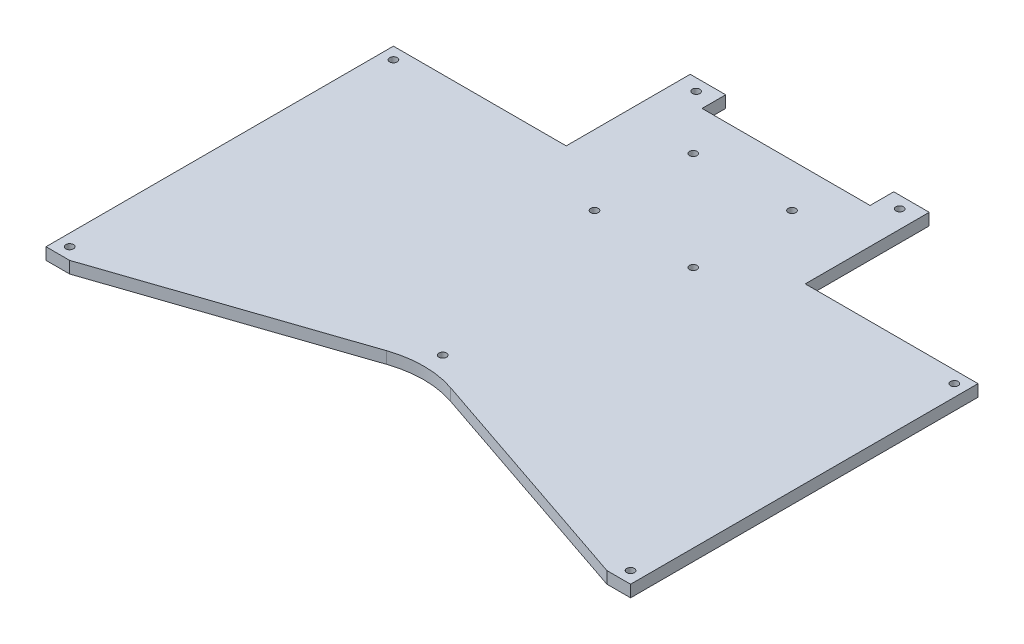
SolidWorks part; units mm, degrees
material "ABS PC"
ref_plane "Plan de face" through (0, 0, 0) normal (0, 0, 1) x (1, 0, 0)
ref_plane "Plan de dessus" through (0, 0, 0) normal (0, 1, 0) x (1, 0, 0)
ref_plane "Plan de droite" through (0, 0, 0) normal (1, 0, 0) x (0, 0, -1)
sketch "Esquisse1" plane through (0, 0, 0) normal (0, 1, 0) x (1, 0, 0)
  line L1 (-50.5, 31.2) -> (-35.5, 31.2)
  line L2 (123.5, -21.2) -> (123.5, -168)
  line L4 (123.5, -168) -> (113.5, -168)
  line L5 (-123.5, -168) -> (-123.5, -21.2)
  line L6 (-113.5, -168) -> (-123.5, -168)
  line L7 (-113.5, -168) -> (-13.4883, -134.0848)
  line L11 (13.4883, -134.0848) -> (113.5, -168)
  line L12 (-123.5, -21.2) -> (-50.5, -21.2)
  line L13 (-55.5, -15) -> (-55.5, 15) construction
  line L14 (123.5, -21.2) -> (50.5, -21.2)
  line L15 (50.5, -21.2) -> (50.5, 31.2)
  line L16 (-50.5, -21.2) -> (-50.5, 31.2)
  line L17 (55.5, 15) -> (55.5, -15) construction
  line L18 (-35.5, 31.2) -> (-35.5, 21.2)
  line L19 (-35.5, 21.2) -> (35.5, 21.2)
  line L20 (35.5, 21.2) -> (35.5, 31.2)
  line L21 (35.5, 31.2) -> (50.5, 31.2)
  line L22 (-114.5, 31.2) -> (114.5, 31.2) construction
  line L23 (-114.5, 21.2) -> (114.5, 21.2) construction
  arc A0 (-13.4883, -134.0848) -> (13.4883, -134.0848) centre (0, -173.86) cw
  arc A1 (-13.4073, -138.8386) -> (13.4073, -138.8386) centre (0, -173.86) ccw construction
  dimension "D1" = 42
  dimension "D2" = 5
  dimension "D3" = 5
  dimension "D4" = 15
extrude "Boss.-Extru.1" add sketch "Esquisse1" along normal blind 5
sketch "Esquisse2" plane through (0, 0, 0) normal (0, -1, 0) x (1, 0, 0)
  line L0 (35.5, -26.2) -> (50.5, -26.2) construction
  line L1 (35.5, -31.2) -> (35.5, -21.2) construction
  line L2 (50.5, 21.2) -> (50.5, -31.2) construction
  line L4 (-35.5, -21.2) -> (-35.5, -31.2) construction
  line L5 (-35.5, -26.2) -> (-50.5, -26.2) construction
  line L6 (-50.5, -31.2) -> (-50.5, 21.2) construction
  circle A0 centre (-118.5, 163) radius 1.6
  circle A1 centre (118.5, 163) radius 1.6
  circle A2 centre (118.5, 26.2) radius 1.6
  circle A3 centre (-118.5, 26.2) radius 1.6
  circle A4 centre (43, -26.2) radius 1.6
  circle A5 centre (-43, -26.2) radius 1.6
  circle A6 centre (20.8597, 38.8597) radius 1.6
  circle A7 centre (-20.8597, 38.8597) radius 1.6
  circle A8 centre (-20.8597, -2.8597) radius 1.6
  circle A9 centre (20.8597, -2.8597) radius 1.6
  circle A10 centre (0, 123.86) radius 1.6
  circle A11 centre (0, 173.86) radius 37.5 construction
  dimension "D1" = 3.2
  dimension "D2" = 50
extrude "Enlèv. mat.-Extru.1" cut sketch "Esquisse2" against normal through all
